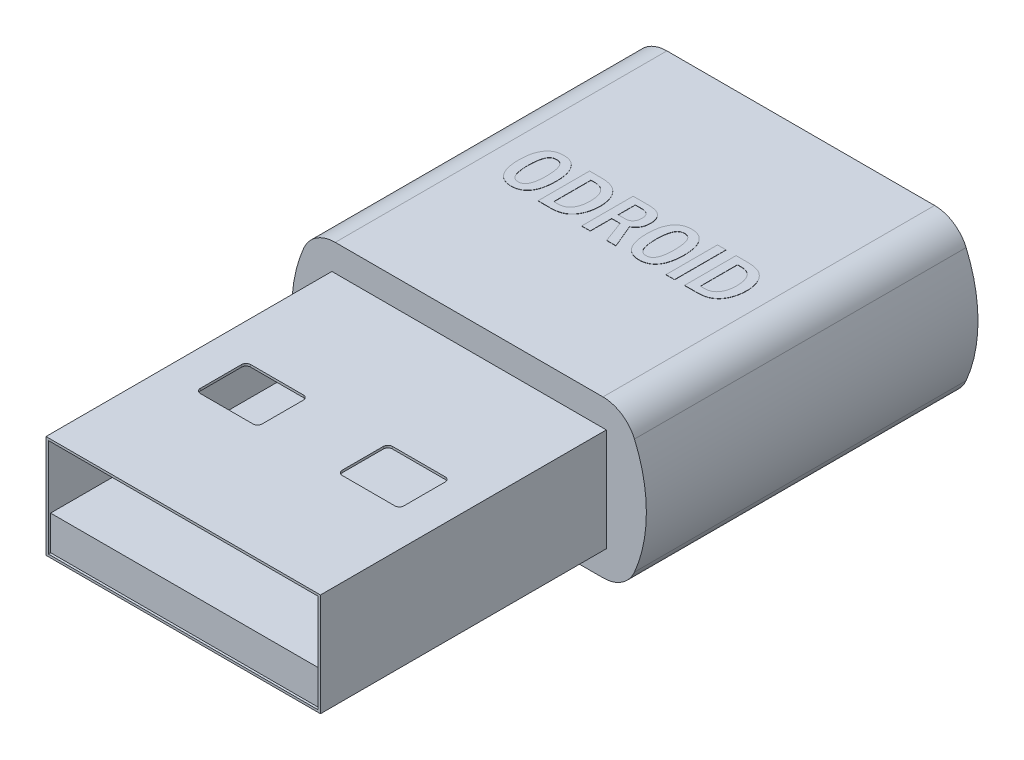
SolidWorks part; units mm, degrees
ref_plane "Front Plane" through (0, 0, 0) normal (0, 0, 1) x (1, 0, 0)
ref_plane "Top Plane" through (0, 0, 0) normal (0, 1, 0) x (1, 0, 0)
ref_plane "Right Plane" through (0, 0, 0) normal (1, 0, 0) x (0, 0, -1)
sketch "Sketch1" plane through (0, 0, 0) normal (0, 0, 1) x (1, 0, 0)
  line L1 (-5.853, 3.425) -> (5.853, 3.425)
  line L3 (-5.853, -3.425) -> (5.853, -3.425)
  arc A0 (-7.2306, 2.5185) -> (-7.2306, -2.5185) centre (-1.3847, 0) ccw
  arc A1 (7.2306, 2.5185) -> (7.2306, -2.5185) centre (1.3847, 0) cw
  arc A2 (5.853, -3.425) -> (7.2306, -2.5185) centre (5.853, -1.925) ccw
  arc A3 (5.853, 3.425) -> (7.2306, 2.5185) centre (5.853, 1.925) cw
  arc A4 (-7.2306, -2.5185) -> (-5.853, -3.425) centre (-5.853, -1.925) ccw
  arc A5 (-5.853, 3.425) -> (-7.2306, 2.5185) centre (-5.853, 1.925) ccw
  point P7 (-7.75, 0)
  point P8 (7.75, 0)
  point P13 (6.75, 3.425)
  point P18 (-6.75, 3.425)
  dimension "D7" = 1.5
  dimension "D1" = 6.85
  dimension "D2" = 13.5
  dimension "D3" = 6.75
  dimension "D4" = 3.425
  dimension "D5" = 1
  dimension "D6" = 1
extrude "Boss-Extrude1" add sketch "Sketch1" against normal blind 14.5
sketch "Sketch2" plane through (0, 0, 0) normal (0, 0, 1) x (1, 0, 0)
  line L1 (-6, 2.25) -> (6, 2.25)
  line L2 (-6, 2.25) -> (-6, -2.25)
  line L3 (-6, -2.25) -> (6, -2.25)
  line L4 (6, 2.25) -> (6, -2.25)
  line L5 (-5.9, 2.15) -> (5.9, 2.15)
  line L6 (-5.9, 2.15) -> (-5.9, -2.15)
  line L7 (-5.9, -2.15) -> (5.9, -2.15)
  line L8 (5.9, 2.15) -> (5.9, -2.15)
  dimension "D1" = 12
  dimension "D2" = 6
  dimension "D3" = 4.5
  dimension "D4" = 2.25
  dimension "D5" = 0.1
  dimension "D6" = 0.1
  dimension "D7" = 0.1
  dimension "D8" = 0.1
extrude "Boss-Extrude2" add sketch "Sketch2" along normal blind 12.5
sketch "Sketch3" plane through (0, 0, 0) normal (0, 0, 1) x (1, 0, 0)
  line L0 (5.9, -2.15) -> (5.9, 2.15) construction
  line L1 (-5.9, -2.15) -> (5.9, -2.15)
  line L2 (-5.9, -2.15) -> (-5.9, -0.65)
  line L3 (-5.9, -0.65) -> (5.9, -0.65)
  line L4 (5.9, -2.15) -> (5.9, -0.65)
  dimension "D1" = 1.5
extrude "Boss-Extrude3" add sketch "Sketch3" along normal blind 12.4
sketch "Sketch4" plane through (0, 2.25, 0) normal (0, 1, 0) x (1, 0, 0)
  line L1 (-4.25, -5.3) -> (-1.95, -5.3)
  line L2 (-4.45, -5.5) -> (-4.45, -7.3)
  line L3 (-4.25, -7.5) -> (-1.95, -7.5)
  line L4 (-1.75, -5.5) -> (-1.75, -7.3)
  line L5 (1.95, -5.3) -> (4.25, -5.3)
  line L6 (1.75, -5.5) -> (1.75, -7.3)
  line L7 (1.95, -7.5) -> (4.25, -7.5)
  line L8 (4.45, -5.5) -> (4.45, -7.3)
  arc A0 (4.25, -7.5) -> (4.45, -7.3) centre (4.25, -7.3) ccw
  arc A1 (4.25, -5.3) -> (4.45, -5.5) centre (4.25, -5.5) cw
  arc A2 (1.75, -7.3) -> (1.95, -7.5) centre (1.95, -7.3) ccw
  arc A3 (1.95, -5.3) -> (1.75, -5.5) centre (1.95, -5.5) ccw
  arc A4 (-4.45, -7.3) -> (-4.25, -7.5) centre (-4.25, -7.3) ccw
  arc A5 (-1.95, -7.5) -> (-1.75, -7.3) centre (-1.95, -7.3) ccw
  arc A6 (-1.95, -5.3) -> (-1.75, -5.5) centre (-1.95, -5.5) cw
  arc A7 (-4.25, -5.3) -> (-4.45, -5.5) centre (-4.25, -5.5) ccw
  point P13 (4.45, -5.3)
  point P16 (1.75, -7.5)
  point P19 (1.75, -5.3)
  point P22 (-4.45, -7.5)
  point P27 (-1.75, -5.3)
  point P30 (-4.45, -5.3)
  dimension "D9" = 0.2
  dimension "D1" = 2.7
  dimension "D2" = 2.7
  dimension "D3" = 2.2
  dimension "D4" = 2.2
  dimension "D5" = 3.5
  dimension "D6" = 1.75
  dimension "D7" = 5.3
  dimension "D8" = 5.3
extrude "Cut-Extrude1" cut sketch "Sketch4" against normal blind 0.5
sketch "Sketch5" plane through (0, 3.425, 0) normal (0, 1, 0) x (1, 0, 0)
  line L0 (-5.5, 6) -> (5.5, 6) construction
  text T0 "ODROID" font "Franklin Gothic Medium Cond" height 2.25
  dimension "D1" = 11
  dimension "D2" = 5.5
  dimension "D3" = 6
extrude "Boss-Extrude4" add sketch "Sketch5" along normal blind 0.01
